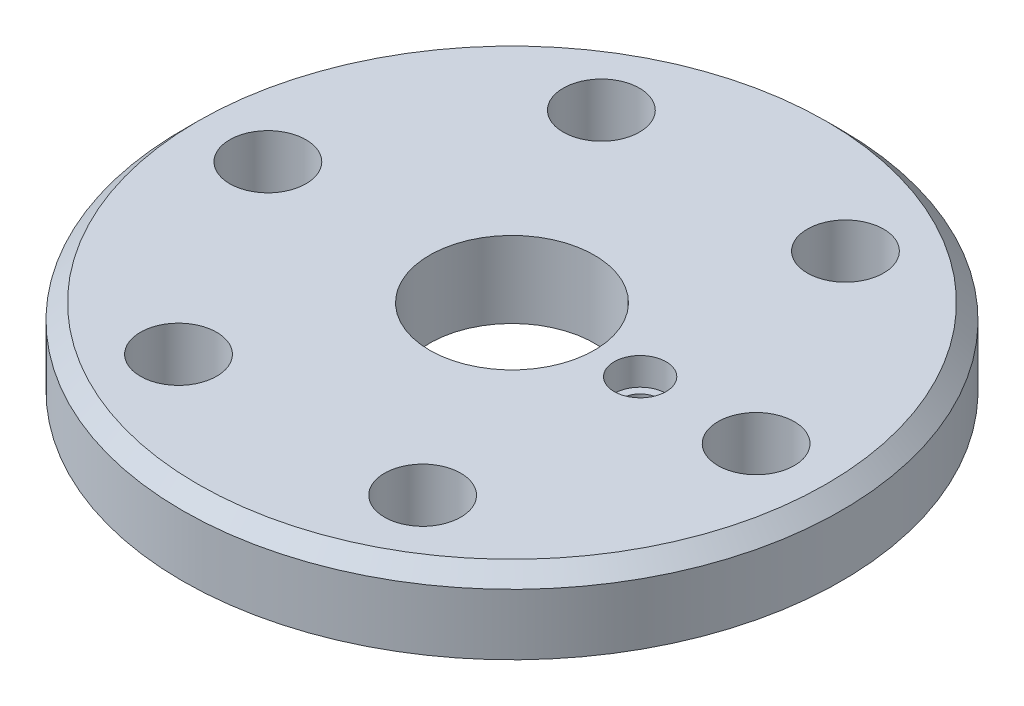
SolidWorks part; units mm, degrees
material "Gray Cast Iron"
ref_plane "Front Plane" through (0, 0, 0) normal (0, 0, 1) x (1, 0, 0)
ref_plane "Top Plane" through (0, 0, 0) normal (0, 1, 0) x (1, 0, 0)
ref_plane "Right Plane" through (0, 0, 0) normal (1, 0, 0) x (0, 0, -1)
sketch "Sketch1" plane through (0, 0, 0) normal (0, 1, 0) x (1, 0, 0)
  line L0 (0, 59.6107) -> (0, -67.683) construction
  line L1 (-140.3455, 0) -> (146.5311, 0) construction
  line L2 (40, 69.282) -> (0, 0)
  circle A0 centre (0, 0) radius 27
  circle A1 centre (0, 0) radius 80 construction
  circle A3 centre (0, 0) radius 108
  circle A4 centre (40, 69.282) radius 12.5
  circle A5 centre (80, 0) radius 12.5
  circle A6 centre (40, -69.282) radius 12.5
  circle A7 centre (-40, -69.282) radius 12.5
  circle A8 centre (-80, 0) radius 12.5
  circle A9 centre (-40, 69.282) radius 12.5
  point P23 (0, 0)
  dimension "D1" = 54
  dimension "D2" = 160
  dimension "D3" = 216
  dimension "D4" = 25
  dimension "D5" = 30
  dimension "D7" = 40
  dimension "D8" = 80
  dimension "D6" = 6
extrude "Boss-Extrude1" add sketch "Sketch1" along normal blind 25
chamfer "Chamfer1" distance 5 angle 45 1 edges at (0, 25, 108)
sketch "Sketch2" plane through (0, 0, 0) normal (0, -1, 0) x (1, 0, 0)
  circle A0 centre (0, 0) radius 42 construction
  dimension "D1" = 84
hole_wizard "M12x0.35 Tapped Hole2" positions "3DSketch1" profile "Sketch3" tap size "M12x0.35" standard "DIN" end condition through all
sketch3d "3DSketch1"
  circle A0 centre (0, 0, 0) radius 42 construction
  point P0 (42, 0, 0)
  point P4 (0, -42, 0)
sketch "Sketch3" plane through (42, 0, 0) normal (1, 0, 0) x (0, 0, -1)
  line L0 (0, 0) -> (0, 25)
  line L1 (0, 25) -> (5.825, 25)
  line L2 (5.825, 25) -> (5.825, 0)
  line L5 (5.825, 0) -> (0, 0)
  line L11 (0, -6.35) -> (0, 107.95) construction
  dimension "Thru Tap Drill Dia." = 11.65
  dimension "Thru Tap Drill Depth" = 25
cosmetic thread "Hole Thread1" parameters "D2"=12
sketch "Sketch4" plane through (0, 25, 0) normal (0, 1, 0) x (1, 0, 0)
  circle A0 centre (42, 0) radius 8.5
  dimension "D1" = 17
extrude "Cut-Extrude2" cut sketch "Sketch4" against normal blind 9
